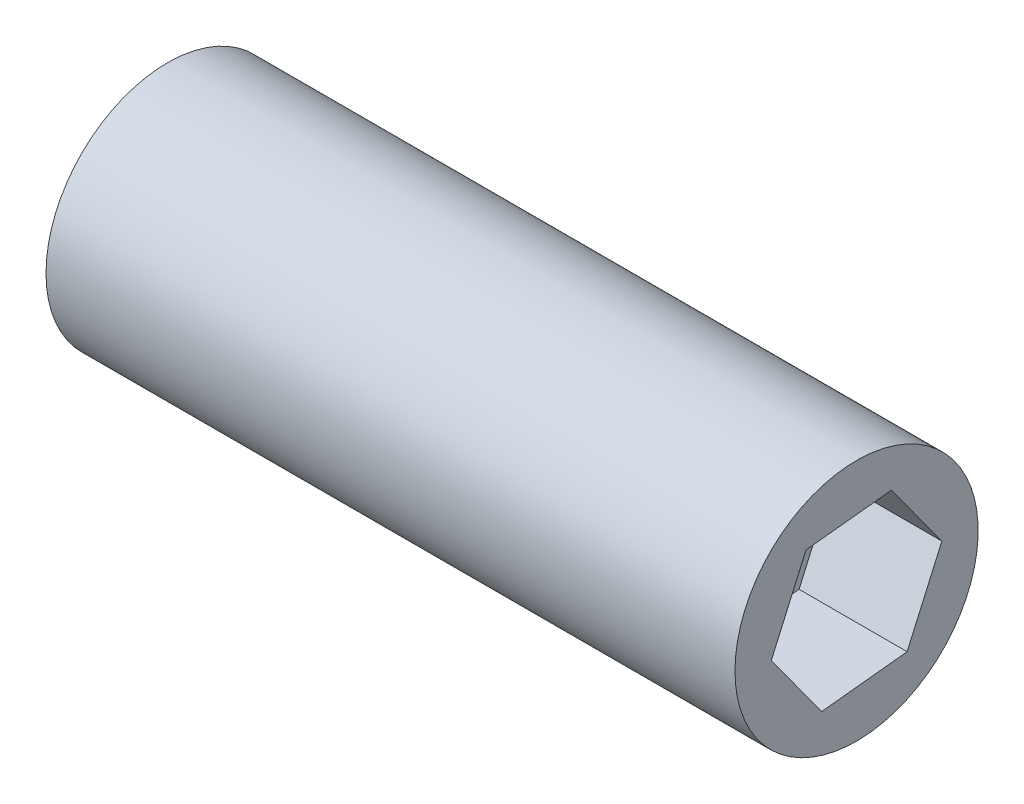
SolidWorks part; units mm, degrees
ref_plane "Front Plane" through (0, 0, 0) normal (0, 0, 1) x (1, 0, 0)
ref_plane "Top Plane" through (0, 0, 0) normal (0, 1, 0) x (1, 0, 0)
ref_plane "Right Plane" through (0, 0, 0) normal (1, 0, 0) x (0, 0, -1)
sketch "Sketch1" plane through (0, 0, 0) normal (1, 0, 0) x (0, 0, -1)
  circle A0 centre (0, 0) radius 4.5
  dimension "D1" = 9
extrude "Boss-Extrude1" add sketch "Sketch1" along normal up to surface (12.75 mm away) and the other way up to surface (12.75 mm away)
sketch "Sketch2" plane through (-12.75, 0, 0) normal (-1, 0, 0) x (0, 0, 1)
  line L1 (3.1575, -0.3373) -> (1.8708, 2.5658)
  line L2 (1.8708, 2.5658) -> (-1.2867, 2.9031)
  line L3 (-1.2867, 2.9031) -> (-3.1575, 0.3373)
  line L4 (-3.1575, 0.3373) -> (-1.8708, -2.5658)
  line L5 (-1.8708, -2.5658) -> (1.2867, -2.9031)
  line L6 (1.2867, -2.9031) -> (3.1575, -0.3373)
  circle A0 centre (0, 0) radius 2.75 construction
  dimension "D1" = 5.5
extrude "Cut-Extrude1" cut sketch "Sketch2" against normal blind 4
mirror "Mirror1" about plane through (0, 0, 0) normal (1, 0, 0) of "Cut-Extrude1"
sketch "Sketch4" plane through (0, 0, 0) normal (1, 0, 0) x (0, 0, -1)
  circle A0 centre (0, 0) radius 1.6
  dimension "D1" = 3.2
extrude "Cut-Extrude3" cut sketch "Sketch4" against normal up to surface and the other way up to surface up to face at (-8.75, 0, 0) other way up to face at (8.75, 0, 0)
